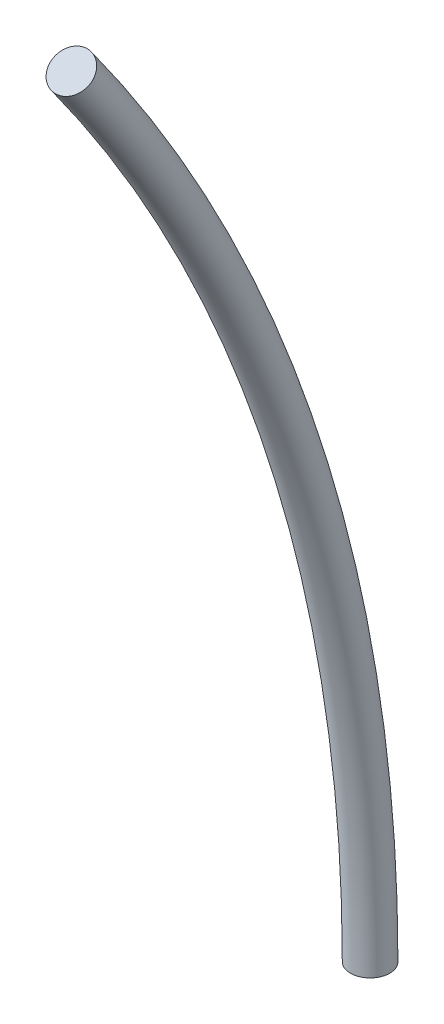
SolidWorks part; units mm, degrees
material "PMMA"
ref_plane "Front" through (0, 0, 0) normal (0, 0, 1) x (1, 0, 0)
ref_plane "Top" through (0, 0, 0) normal (0, 1, 0) x (1, 0, 0)
ref_plane "Right" through (0, 0, 0) normal (1, 0, 0) x (0, 0, -1)
sketch "Sketch1" plane through (0, 0, 0) normal (1, 0, 0) x (0, 0, -1)
  line L0 (0, 0) -> (0, -16.456) construction
  arc A0 (0, 0) -> (-45.537, 140.3487) centre (-239.0515, 0) ccw
  dimension "D1" = 150
sketch "Sketch2" plane through (0, 0, 0) normal (0, 1, 0) x (1, 0, 0)
  circle A0 centre (0, 0) radius 3
  dimension "D1" = 6
sweep "Sweep1" add profiles "Sketch2" path "Sketch1"
